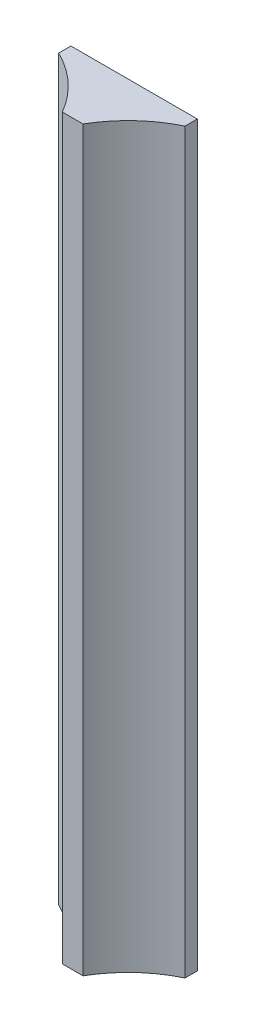
SolidWorks part; units mm, degrees
ref_plane "Front" through (0, 0, 0) normal (0, 0, 1) x (1, 0, 0)
ref_plane "Top" through (0, 0, 0) normal (0, 1, 0) x (1, 0, 0)
ref_plane "Right" through (0, 0, 0) normal (1, 0, 0) x (0, 0, -1)
sketch "Sketch1" plane through (0, 0, 0) normal (0, 1, 0) x (1, 0, 0)
  line L0 (-0.8397, 0) -> (0.8397, 0)
  line L1 (5.1411, 4) -> (5.1411, 5)
  line L2 (5.1411, 5) -> (-5.1411, 5)
  line L3 (-5.1411, 5) -> (-5.1411, 4)
  arc A0 (0.8397, 0) -> (5.1411, 4) centre (9.5, -5) cw
  arc A1 (-5.1411, 4) -> (-0.8397, 0) centre (-9.5, -5) cw
  point P9 (0, 5)
  point P10 (0, 0)
  dimension "D1" = 10
  dimension "D6" = 5
  dimension "D2" = 19
  dimension "D3" = 10
  dimension "D4" = 1
extrude "Boss-Extrude1" add sketch "Sketch1" along normal mid plane 60
sketch "Sketch3" plane through (0, 0, -5) normal (0, 0, -1) x (-1, 0, 0)
  line L0 (0, -30) -> (0, 30) construction
  line L1 (-5.1411, -30) -> (5.1411, -30) construction
  line L2 (-5.1411, 30) -> (5.1411, 30) construction
  point P6 (0, 0)
  dimension "D2" = 30
hole_wizard "Tapped Hole for M2.5x0.45 Helicoil1" [suppressed] positions "3DSketch1" profile "Sketch4" tap size "M2.5x0.45" standard "Helicoil® Metric"
sketch3d "3DSketch1"
  point P0 (0, 0, -5)
cosmetic thread "Hole Thread2" [suppressed] parameters "D1"=3, "D2"=3.145
sketch "Sketch4" plane through (0, 0, -5) normal (1, 0, 0) x (0, 1, 0)
  line L0 (0, 0) -> (0, 4.7661)
  line L1 (0, 4.7661) -> (1.275, 4)
  line L2 (1.275, 4) -> (1.275, 0)
  line L5 (1.275, 0) -> (0, 0)
  line L10 (0, 4.7661) -> (-1.275, 4) construction
  line L11 (0, -6.35) -> (0, 107.95) construction
  dimension "Tap Drill Dia." = 2.55
  dimension "Tap Drill Depth" = 4
  dimension "Drill Angle" = 118
hole_wizard "Ø1.2 (1.2) Diameter Hole1" [suppressed] positions "3DSketch2" profile "Sketch5" hole size "Ø1.2" standard "ANSI Metric"
sketch3d "3DSketch2"
  point P0 (0, 0, -5)
sketch "Sketch5" plane through (0, 0, -5) normal (1, 0, 0) x (0, 1, 0)
  line L0 (0, 0) -> (0, 6.8105)
  line L1 (0, 6.8105) -> (0.6, 6.45)
  line L2 (0.6, 6.45) -> (0.6, 0)
  line L5 (0.6, 0) -> (0, 0)
  line L10 (0, 6.8105) -> (-0.6, 6.45) construction
  line L11 (0, -6.35) -> (0, 107.95) construction
  dimension "Hole Dia." = 1.2
  dimension "Hole Depth" = 6.45
  dimension "Drill Angle" = 118
